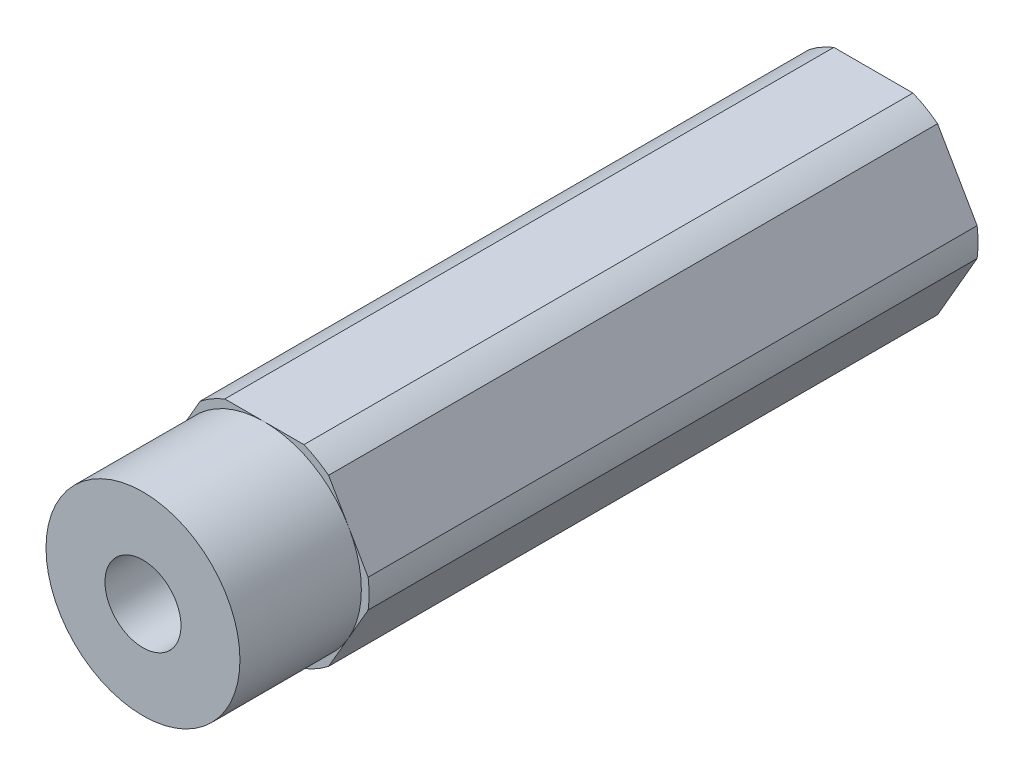
SolidWorks part; units mm, degrees
ref_plane "Front Plane" through (0, 0, 0) normal (0, 0, 1) x (1, 0, 0)
ref_plane "Top Plane" through (0, 0, 0) normal (0, 1, 0) x (1, 0, 0)
ref_plane "Right Plane" through (0, 0, 0) normal (1, 0, 0) x (0, 0, -1)
sketch "Sketch1" plane through (0, 0, 0) normal (0, 0, 1) x (1, 0, 0)
  line L1 (7.3323, 0) -> (3.6662, 6.35)
  line L2 (3.6662, 6.35) -> (-3.6662, 6.35)
  line L3 (-3.6662, 6.35) -> (-7.3323, 0)
  line L4 (-7.3323, 0) -> (-3.6662, -6.35)
  line L5 (-3.6662, -6.35) -> (3.6662, -6.35)
  line L6 (3.6662, -6.35) -> (7.3323, 0)
  circle A0 centre (0, 0) radius 6.35 construction
  dimension "D1" = 12.7
extrude "Boss-Extrude1" add sketch "Sketch1" along normal mid plane 47.8282
sketch "Sketch3" plane through (0, 0, 23.9141) normal (0, 0, 1) x (1, 0, 0)
  circle A0 centre (0, 0) radius 6.35
extrude "Cut-Extrude2" cut sketch "Sketch3" against normal blind 7.9502 flip side to cut
sketch "Sketch4" plane through (0, 0, 23.9141) normal (0, 0, 1) x (1, 0, 0)
  circle A0 centre (0, 0) radius 6.858
  dimension "D1" = 13.716
extrude "Cut-Extrude3" cut sketch "Sketch4" against normal through all flip side to cut
sketch "Sketch5" plane through (0, 0, 23.9141) normal (0, 0, 1) x (1, 0, 0)
  circle A0 centre (0, 0) radius 2.4892
  dimension "D1" = 4.9784
extrude "Cut-Extrude4" cut sketch "Sketch5" against normal through all
equation "\"D1@Boss-Extrude1\"=1.87300+0.01"
